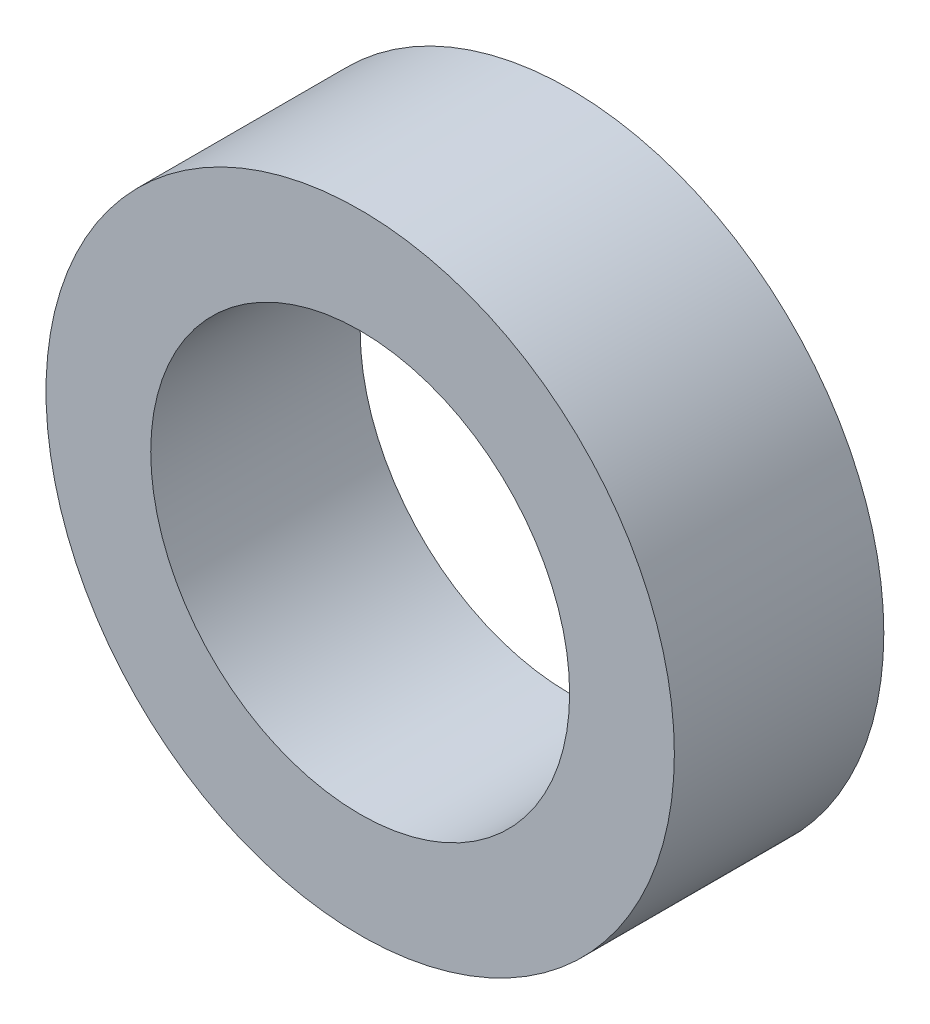
SolidWorks part; units mm, degrees
ref_plane "Front Plane" through (0, 0, 0) normal (0, 0, 1) x (1, 0, 0)
ref_plane "Top Plane" through (0, 0, 0) normal (0, 1, 0) x (1, 0, 0)
ref_plane "Right Plane" through (0, 0, 0) normal (1, 0, 0) x (0, 0, -1)
sketch "Sketch1" plane through (0, 0, 0) normal (0, 0, 1) x (1, 0, 0)
  circle A0 centre (0, 0) radius 4
  circle A1 centre (0, 0) radius 6
  dimension "D1" = 8
  dimension "D2" = 12
extrude "Boss-Extrude1" add sketch "Sketch1" along normal mid plane 4
